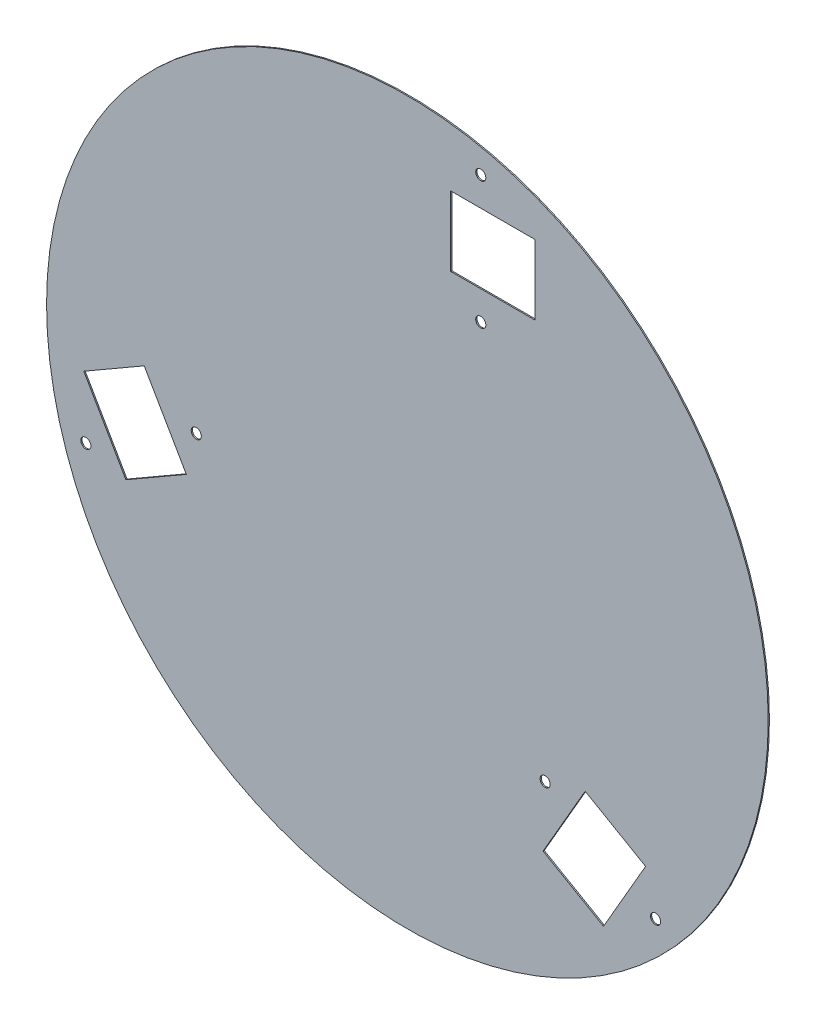
SolidWorks part; units mm, degrees
material "Acier non allié"
ref_plane "Plan de face" through (0, 0, 0) normal (0, 0, 1) x (1, 0, 0)
ref_plane "Plan de dessus" through (0, 0, 0) normal (0, 1, 0) x (1, 0, 0)
ref_plane "Plan de droite" through (0, 0, 0) normal (1, 0, 0) x (0, 0, -1)
sketch "Esquisse8" [suppressed] plane through (0, 0, 0) normal (0, 0, 1) x (1, 0, 0)
  line B0 (-127.0632, 47.6636) -> (-120.3316, 47.6636)
  line B1 (-120.3316, 50.4215) -> (-120.3316, 47.6636)
  line B2 (-127.0632, 50.4215) -> (-120.3316, 50.4215)
  line B3 (-127.0632, 50.4215) -> (-127.0632, 47.6636)
  line B4 (-145.8689, 41.621) -> (-145.8689, 44.3023)
  line B5 (-132.9996, 41.621) -> (-145.8689, 41.621)
  line B6 (-132.9996, 55.9755) -> (-132.9996, 41.621)
  line B7 (-136.1141, 55.9755) -> (-132.9996, 55.9755)
  line B8 (-136.1141, 44.3023) -> (-136.1141, 55.9755)
  line B9 (-145.8689, 44.3023) -> (-136.1141, 44.3023)
  line B10 (-166.6205, 55.9755) -> (-166.6205, 53.1907)
  line B11 (-153.5296, 53.1907) -> (-166.6205, 53.1907)
  line B12 (-153.5296, 55.9755) -> (-153.5296, 53.1907)
  line B13 (-153.5296, 55.9755) -> (-166.6205, 55.9755)
  line B14 (-211.399, 53.1907) -> (-198.3081, 53.1907)
  line B15 (-198.3081, 55.9585) -> (-198.3081, 53.1907)
  line B16 (-211.399, 55.9585) -> (-198.3081, 55.9585)
  line B17 (-211.399, 55.9585) -> (-211.399, 53.1907)
  line B18 (-211.399, 41.621) -> (-198.3081, 41.621)
  line B19 (-198.3081, 44.2943) -> (-198.3081, 41.621)
  line B20 (-207.9561, 44.2943) -> (-198.3081, 44.2943)
  line B21 (-207.9561, 47.6636) -> (-207.9561, 44.2943)
  line B22 (-207.9561, 47.6636) -> (-202.1941, 47.6636)
  line B23 (-202.1941, 50.4215) -> (-202.1941, 47.6636)
  line B24 (-211.399, 50.4215) -> (-202.1941, 50.4215)
  line B25 (-211.399, 50.4215) -> (-211.399, 41.621)
  line B26 (-167.5588, 94.5889) -> (-165.466, 94.5889)
  line B27 (-168.2446, 93.9031) -> (-168.2446, 93.8927)
  line B28 (-168.2446, 93.8927) -> (-164.7802, 93.8927)
  line B29 (-164.7802, 93.9031) -> (-164.7802, 93.8927)
  line B30 (-179.5199, 94.5889) -> (-179.5199, 93.8927)
  line B31 (-176.2471, 93.8927) -> (-179.5199, 93.8927)
  line B32 (-176.2471, 94.5889) -> (-176.2471, 93.8927)
  line B33 (-179.5199, 94.5889) -> (-176.2471, 94.5889)
  line B34 (-187.9744, 91.0002) -> (-184.8699, 91.0002)
  line B35 (-184.8699, 91.6706) -> (-184.8699, 91.0002)
  line B36 (-187.2953, 91.6706) -> (-184.8699, 91.6706)
  line B37 (-187.2953, 94.5889) -> (-187.2953, 91.6706)
  line B38 (-187.9744, 94.5889) -> (-187.2953, 94.5889)
  line B39 (-187.9744, 94.5889) -> (-187.9744, 91.0002)
  line B40 (-182.8118, 91.0002) -> (-182.1258, 91.0002)
  line B41 (-182.1258, 94.5889) -> (-182.1258, 91.0002)
  line B42 (-182.8118, 94.5889) -> (-182.1258, 94.5889)
  line B43 (-182.8118, 94.5889) -> (-182.8118, 91.0002)
  line B44 (-191.2034, 93.2004) -> (-191.2034, 92.5109)
  line B45 (-193.5046, 93.2004) -> (-191.2034, 93.2004)
  line B46 (-193.5046, 93.2004) -> (-193.5046, 91.0002)
  line B47 (-193.5046, 91.0002) -> (-190.2319, 91.0002)
  line B48 (-190.2319, 91.6706) -> (-190.2319, 91.0002)
  line B49 (-192.6439, 91.6706) -> (-190.2319, 91.6706)
  line B50 (-192.6439, 92.5109) -> (-192.6439, 91.6706)
  line B51 (-192.6439, 92.5109) -> (-191.2034, 92.5109)
  line B52 (-193.5046, 93.8927) -> (-190.2319, 93.8927)
  line B53 (-190.2319, 94.5889) -> (-190.2319, 93.8927)
  line B54 (-193.5046, 94.5889) -> (-190.2319, 94.5889)
  line B55 (-193.5046, 94.5889) -> (-193.5046, 93.8927)
  line B56 (-217.8342, 92.5109) -> (-216.3937, 92.5109)
  line B57 (-216.3937, 93.2004) -> (-216.3937, 92.5109)
  line B58 (-218.6949, 93.2004) -> (-216.3937, 93.2004)
  line B59 (-218.6949, 93.2004) -> (-218.6949, 91.0002)
  line B60 (-218.6949, 91.0002) -> (-215.4222, 91.0002)
  line B61 (-215.4222, 91.6686) -> (-215.4222, 91.0002)
  line B62 (-217.8342, 91.6686) -> (-215.4222, 91.6686)
  line B63 (-217.8342, 92.5109) -> (-217.8342, 91.6686)
  line B64 (-218.6949, 93.8927) -> (-215.4222, 93.8927)
  line B65 (-215.4222, 94.5889) -> (-215.4222, 93.8927)
  line B66 (-218.6949, 94.5889) -> (-215.4222, 94.5889)
  line B67 (-218.6949, 94.5889) -> (-218.6949, 93.8927)
  line B68 (-153.6274, 100.4538) -> (-163.9488, 110.7564)
  line B69 (-150.6931, 103.3934) -> (-153.6274, 100.4538)
  line B70 (-158.6273, 111.3265) -> (-150.6931, 103.3934)
  line B71 (-150.6981, 119.2702) -> (-158.6273, 111.3265)
  line B72 (-153.6179, 122.1847) -> (-150.6981, 119.2702)
  line B73 (-163.9498, 111.834) -> (-153.6179, 122.1847)
  line B74 (-212.5077, 91.0002) -> (-210.4149, 91.0002)
  line B75 (-209.7291, 92.5146) -> (-209.7291, 91.686)
  line B76 (-213.1935, 93.2004) -> (-210.4149, 93.2004)
  line B77 (-213.1935, 93.2004) -> (-213.1935, 93.1967)
  line B78 (-212.5077, 92.5109) -> (-210.4149, 92.5109)
  line B79 (-210.4149, 92.5109) -> (-210.4149, 91.6686)
  line B80 (-212.5053, 91.6686) -> (-210.4149, 91.6686)
  line B81 (-212.5053, 92.1003) -> (-212.5053, 91.6686)
  line B82 (-213.1935, 92.1003) -> (-212.5053, 92.1003)
  line B83 (-213.1935, 91.686) -> (-213.1935, 92.1003)
  line B84 (-195.2147, 94.5889) -> (-195.2147, 93.8927)
  line B85 (-199.0185, 94.5889) -> (-195.2147, 94.5889)
  line B86 (-199.0185, 94.5889) -> (-199.0185, 93.8927)
  line B87 (-199.0185, 93.8927) -> (-197.4712, 93.8927)
  line B88 (-197.4712, 93.8927) -> (-197.4712, 91.0002)
  line B89 (-197.4712, 91.0002) -> (-196.7942, 91.0002)
  line B90 (-196.7942, 93.8927) -> (-196.7942, 91.0002)
  line B91 (-196.7942, 93.8927) -> (-195.2147, 93.8927)
  line B92 (-161.3569, 85.3255) -> (-157.5898, 83.0055)
  line B93 (-157.5898, 83.0055) -> (-157.5898, 87.227)
  line B94 (-161.3569, 87.227) -> (-157.5898, 87.227)
  line B95 (-161.3569, 87.227) -> (-161.3569, 85.3255)
  line B96 (-150.3507, 78.4647) -> (-150.3507, 69.7508)
  line B97 (-145.0595, 72.3959) -> (-150.3507, 78.4647)
  line B98 (-139.5033, 78.4647) -> (-145.0595, 72.3959)
  line B99 (-139.5033, 69.7508) -> (-139.5033, 78.4647)
  line B100 (-135.8832, 69.7508) -> (-139.5033, 69.7508)
  line B101 (-135.8832, 87.6265) -> (-135.8832, 69.7508)
  line B102 (-145.0509, 77.9984) -> (-135.8832, 87.6265)
  line B103 (-154.0819, 87.8508) -> (-145.0509, 77.9984)
  line B104 (-154.0819, 69.7508) -> (-154.0819, 87.8508)
  line B105 (-154.0819, 69.7508) -> (-150.3507, 69.7508)
  line B106 (-121.0636, 82.5326) -> (-116.4642, 82.5326)
  line B107 (-132.5484, 82.5326) -> (-127.949, 82.5326)
  line B108 (-238.7768, 62.4441) -> (-69.387, 62.4441)
  line B109 (-69.387, 63.243) -> (-69.387, 62.4441)
  line B110 (-238.7768, 63.243) -> (-69.387, 63.243)
  line B111 (-238.7768, 63.243) -> (-238.7768, 62.4441)
  line B112 (-91.2664, 69.7508) -> (-87.3469, 69.7508)
  line B113 (-87.3469, 82.5326) -> (-87.3469, 69.7508)
  line B114 (-91.2664, 82.5326) -> (-87.3469, 82.5326)
  line B115 (-91.2664, 69.7508) -> (-91.2664, 82.5326)
  line B116 (-96.0285, 83.7433) -> (-82.8413, 83.7433)
  line B117 (-82.8413, 83.7433) -> (-82.8413, 87.227)
  line B118 (-96.0285, 87.227) -> (-82.8413, 87.227)
  line B119 (-96.0285, 87.227) -> (-96.0285, 83.7433)
  line B120 (-204.5437, 87.227) -> (-199.3625, 77.1943)
  line B121 (-209.7167, 77.1943) -> (-204.5437, 87.227)
  line B122 (-209.7167, 77.1943) -> (-205.6679, 77.1943)
  line B123 (-204.5437, 79.3746) -> (-205.6679, 77.1943)
  line B124 (-203.4177, 77.1943) -> (-204.5437, 79.3746)
  line B125 (-203.4177, 77.1943) -> (-199.3625, 77.1943)
  line B126 (-213.7549, 76.677) -> (-219.9317, 76.677)
  line B127 (-213.7549, 80.1113) -> (-213.7549, 76.677)
  line B128 (-219.9317, 80.1113) -> (-213.7549, 80.1113)
  line B129 (-219.9317, 82.5326) -> (-219.9317, 80.1113)
  line B130 (-223.6873, 82.5326) -> (-219.9317, 82.5326)
  line B131 (-223.6873, 69.8839) -> (-223.6873, 82.5326)
  line B132 (-219.9317, 69.8839) -> (-223.6873, 69.8839)
  line B133 (-219.9317, 76.677) -> (-219.9317, 69.8839)
  line B134 (-168.2446, 93.2004) -> (-165.466, 93.2004)
  line B135 (-168.2446, 93.2004) -> (-168.2446, 93.1967)
  line B136 (-167.5588, 92.5109) -> (-165.466, 92.5109)
  line B137 (-165.466, 92.5109) -> (-165.466, 91.6686)
  line B138 (-167.5564, 91.6686) -> (-165.466, 91.6686)
  line B139 (-167.5564, 92.1003) -> (-167.5564, 91.6686)
  line B140 (-168.2446, 92.1003) -> (-167.5564, 92.1003)
  line B141 (-168.2446, 91.686) -> (-168.2446, 92.1003)
  line B142 (-167.5588, 91.0002) -> (-165.466, 91.0002)
  line B143 (-164.7802, 92.5146) -> (-164.7802, 91.686)
  line B144 (-213.486, 69.8839) -> (-209.4372, 69.8839)
  line B145 (-208.071, 72.5336) -> (-209.4372, 69.8839)
  line B146 (-208.071, 72.5336) -> (-201.0108, 72.5336)
  line B147 (-199.5737, 69.7508) -> (-201.0108, 72.5336)
  line B148 (-195.5185, 69.7508) -> (-199.5737, 69.7508)
  line B149 (-198.728, 75.9657) -> (-195.5185, 69.7508)
  line B150 (-210.3501, 75.9657) -> (-198.728, 75.9657)
  line B151 (-213.486, 69.8839) -> (-210.3501, 75.9657)
  line B152 (-189.8395, 83.7433) -> (-182.0909, 83.7433)
  line B153 (-184.9396, 86.7348) -> (-186.4712, 87.2271)
  line B154 (-193.6657, 87.2271) -> (-186.4712, 87.2271)
  line B155 (-193.6657, 87.2271) -> (-193.6657, 77.1944)
  line B156 (-193.6657, 77.1944) -> (-186.2925, 77.1944)
  line B157 (-189.8668, 73.1972) -> (-186.3883, 73.1972)
  line B158 (-189.8668, 75.9658) -> (-189.8668, 73.1972)
  line B159 (-193.6657, 75.9658) -> (-189.8668, 75.9658)
  line B160 (-193.6657, 75.9658) -> (-193.6657, 69.7508)
  line B161 (-193.6657, 69.7508) -> (-185.6203, 69.7508)
  line B162 (-185.7395, 82.5327) -> (-181.9445, 82.5327)
  line B163 (-189.8395, 80.2675) -> (-187.1218, 80.2675)
  line B164 (-189.8395, 83.7433) -> (-189.8395, 80.2675)
  line B165 (-174.0652, 83.7433) -> (-165.2782, 83.7433)
  line B166 (-168.6352, 86.6749) -> (-170.5726, 87.227)
  line B167 (-177.791, 87.227) -> (-170.5726, 87.227)
  line B168 (-177.791, 87.227) -> (-177.791, 69.7508)
  line B169 (-177.791, 69.7508) -> (-174.0652, 69.7508)
  line B170 (-174.0652, 69.7508) -> (-174.0652, 75.9657)
  line B171 (-174.0652, 75.9657) -> (-171.5983, 75.9657)
  line B172 (-171.5983, 75.9657) -> (-167.9913, 69.7508)
  line B173 (-167.9913, 69.7508) -> (-163.5264, 69.7508)
  line B174 (-163.5264, 69.7508) -> (-167.7035, 76.7107)
  line B175 (-168.6352, 82.5327) -> (-164.8908, 82.5327)
  line B176 (-174.0652, 79.6101) -> (-170.7412, 79.6101)
  line B177 (-174.0652, 83.7433) -> (-174.0652, 79.6101)
  line B178 (-288.9204, 52.2277) -> (-271.4204, 21.9168)
  line B179 (-271.4204, 21.9168) -> (-246.3057, 36.4168)
  line B180 (-246.3057, 36.4168) -> (-263.8057, 66.7277)
  line B181 (-263.8057, 66.7277) -> (-288.9204, 52.2277)
  line B182 (-80.4996, 5.2399) -> (-97.9996, -25.071)
  line B183 (-97.9996, -25.071) -> (-72.8848, -39.571)
  line B184 (-72.8848, -39.571) -> (-55.3848, -9.2601)
  line B185 (-55.3848, -9.2601) -> (-80.4996, 5.2399)
  line B186 (-136.4026, 164.4207) -> (-101.4026, 164.4207)
  line B187 (-101.4026, 164.4207) -> (-101.4026, 193.4207)
  line B188 (-101.4026, 193.4207) -> (-136.4026, 193.4207)
  line B189 (-136.4026, 193.4207) -> (-136.4026, 164.4207)
  line B190 (-154.5679, 130.5213) -> (-174.01, 111.0768)
  line B191 (-154.4915, 91.5608) -> (-174.01, 111.0768)
  line B192 (-153.4138, 91.5609) -> (-129.6531, 115.3246)
  line B193 (-129.6532, 116.4022) -> (-153.5146, 140.2606)
  line B194 (-178.3529, 116.4968) -> (-154.5922, 140.2605)
  line B195 (-175.9678, 113.0343) -> (-178.3528, 115.4191)
  line B196 (-175.9678, 113.0343) -> (-153.9526, 135.0523)
  line B197 (-153.9526, 135.0523) -> (-134.8557, 115.9579)
  line B198 (-134.8557, 115.9579) -> (-153.9526, 96.8586)
  line B199 (-153.9526, 96.8586) -> (-168.2078, 111.112)
  line B200 (-168.2078, 111.112) -> (-151.1453, 128.1767)
  line B201 (-151.1453, 128.1767) -> (-153.4903, 130.5214)
  line B202 (-161.3569, 69.7508) -> (-157.5898, 69.7508)
  line B203 (-157.5898, 80.7086) -> (-157.5898, 69.7508)
  line B204 (-161.3569, 83.0055) -> (-157.5898, 80.7086)
  line B205 (-161.3569, 83.0055) -> (-161.3569, 69.7508)
  line B206 (-212.2972, 87.227) -> (-223.6873, 87.227)
  line B207 (-223.6873, 87.227) -> (-223.6873, 83.7433)
  line B208 (-223.6873, 83.7433) -> (-212.2972, 83.7433)
  line B209 (-212.2972, 83.7433) -> (-212.2972, 87.227)
  line B210 (-113.2245, 69.7508) -> (-109.375, 69.7508)
  line B211 (-109.375, 79.5134) -> (-109.375, 69.7508)
  line B212 (-97.8943, 69.04) -> (-109.375, 79.5134)
  line B213 (-97.8943, 87.227) -> (-97.8943, 69.04)
  line B214 (-101.6626, 87.227) -> (-97.8943, 87.227)
  line B215 (-101.6626, 87.227) -> (-101.6626, 77.3224)
  line B216 (-101.6626, 77.3224) -> (-113.2245, 87.8508)
  line B217 (-113.2245, 87.8508) -> (-113.2245, 69.7508)
  line B218 (-131.8111, 83.7433) -> (-117.2015, 83.7433)
  line B219 (-201.2358, 91.8292) -> (-200.8109, 91.0002)
  line B220 (-200.8109, 91.0002) -> (-200.0223, 91.0002)
  line B221 (-201.9653, 94.5889) -> (-200.0223, 91.0002)
  line B222 (-202.6502, 94.5889) -> (-201.9653, 94.5889)
  line B223 (-202.6502, 94.5889) -> (-201.5852, 92.5109)
  line B224 (-203.4892, 92.5109) -> (-201.5852, 92.5109)
  line B225 (-204.4284, 91.0002) -> (-203.4892, 92.5109)
  line B226 (-204.4284, 91.0002) -> (-203.6929, 91.0002)
  line B227 (-203.6929, 91.0002) -> (-203.2078, 91.8292)
  line B228 (-203.2078, 91.8292) -> (-201.2358, 91.8292)
  line B229 (-212.5077, 94.5889) -> (-210.4149, 94.5889)
  line B230 (-213.1935, 93.9031) -> (-213.1935, 93.8927)
  line B231 (-213.1935, 93.8927) -> (-209.7291, 93.8927)
  line B232 (-223.0488, 94.5889) -> (-223.8274, 94.5889)
  line B233 (-223.8274, 94.5889) -> (-223.8274, 91.0002)
  line B234 (-223.8274, 91.0002) -> (-220.6101, 91.0002)
  line B235 (-220.6101, 91.0002) -> (-220.6101, 91.6706)
  line B236 (-220.6101, 91.6706) -> (-223.0488, 91.6706)
  line B237 (-223.0488, 91.6706) -> (-223.0488, 94.5889)
  line B238 (-179.5199, 91.0002) -> (-176.2471, 91.0002)
  line B239 (-176.2471, 91.6706) -> (-176.2471, 91.0002)
  line B240 (-178.6591, 91.6706) -> (-176.2471, 91.6706)
  line B241 (-178.6591, 92.5109) -> (-178.6591, 91.6706)
  line B242 (-178.6591, 92.5109) -> (-177.2186, 92.5109)
  line B243 (-177.2186, 93.2004) -> (-177.2186, 92.5109)
  line B244 (-179.5199, 93.2004) -> (-177.2186, 93.2004)
  line B245 (-179.5199, 93.2004) -> (-179.5199, 91.0002)
  line B246 (-170.5964, 93.9031) -> (-170.5964, 93.034)
  line B247 (-174.0031, 94.5889) -> (-171.2822, 94.5889)
  line B248 (-174.0031, 94.5889) -> (-174.0031, 93.8927)
  line B249 (-174.0031, 93.8927) -> (-171.2606, 93.8927)
  line B250 (-171.2606, 93.8927) -> (-171.2606, 92.8686)
  line B251 (-174.0031, 92.8686) -> (-171.2606, 92.8686)
  line B252 (-174.0031, 92.8686) -> (-174.0031, 91.0002)
  line B253 (-174.0031, 91.0002) -> (-173.2075, 91.0002)
  line B254 (-173.2075, 91.0002) -> (-173.2075, 92.3386)
  line B255 (-173.2075, 92.3386) -> (-172.4075, 92.3386)
  line B256 (-172.4075, 92.3386) -> (-171.1064, 91.0002)
  line B257 (-171.1064, 91.0002) -> (-170.1619, 91.0002)
  line B258 (-171.5695, 92.3482) -> (-170.1619, 91.0002)
  line B259 (-171.5695, 92.3482) -> (-171.2822, 92.3482)
  line B260 (-184.4889, 41.6039) -> (-180.44, 41.6039)
  line B261 (-175.5356, 55.9585) -> (-180.44, 41.6039)
  line B262 (-175.5356, 55.9585) -> (-178.8962, 55.9585)
  line B263 (-178.8962, 55.9585) -> (-182.4645, 46.0889)
  line B264 (-186.0328, 55.9585) -> (-182.4645, 46.0889)
  line B265 (-189.3933, 55.9585) -> (-186.0328, 55.9585)
  line B266 (-189.3933, 55.9585) -> (-184.4889, 41.6039)
  line B267 (-219.0597, 44.3023) -> (-228.8145, 44.3023)
  line B268 (-228.8145, 44.3023) -> (-228.8145, 55.9755)
  line B269 (-228.8145, 55.9755) -> (-231.9291, 55.9755)
  line B270 (-231.9291, 55.9755) -> (-231.9291, 41.621)
  line B271 (-231.9291, 41.621) -> (-219.0597, 41.621)
  line B272 (-219.0597, 41.621) -> (-219.0597, 44.3023)
  line B273 (-166.6205, 44.2943) -> (-166.6205, 41.621)
  line B274 (-153.5296, 41.621) -> (-166.6205, 41.621)
  line B275 (-153.5296, 50.4215) -> (-153.5296, 41.621)
  line B276 (-153.5296, 50.4215) -> (-162.7345, 50.4215)
  line B277 (-162.7345, 50.4215) -> (-162.7345, 47.6636)
  line B278 (-156.9725, 47.6636) -> (-162.7345, 47.6636)
  line B279 (-156.9725, 47.6636) -> (-156.9725, 44.2943)
  line B280 (-156.9725, 44.2943) -> (-166.6205, 44.2943)
  line B281 (-100.191, 45.2326) -> (-100.191, 55.9755)
  line B282 (-100.191, 55.9755) -> (-103.5515, 55.9755)
  line B283 (-103.5515, 55.9755) -> (-103.5515, 46.3026)
  line B284 (-104.5675, 45.2866) -> (-109.6721, 45.2866)
  line B285 (-110.6881, 55.9755) -> (-110.6881, 46.3026)
  line B286 (-114.0487, 55.9755) -> (-110.6881, 55.9755)
  line B287 (-114.0487, 55.9755) -> (-114.0487, 45.2326)
  line B288 (-110.4927, 41.6766) -> (-103.747, 41.6766)
  line B289 (-94.6217, 39.3739) -> (-94.6509, 42.6897)
  line B290 (-93.0123, 39.3739) -> (-94.6217, 39.3739)
  line B291 (-93.0123, 40.2363) -> (-93.0123, 39.3739)
  line B292 (-86.3102, 40.2363) -> (-86.3102, 39.3739)
  line B293 (-79.4589, 39.3739) -> (-86.3102, 39.3739)
  line B294 (-85.2131, 50.2165) -> (-79.6533, 49.7729)
  line B295 (-84.6443, 58.1294) -> (-84.6541, 56.0136)
  line B296 (-74.6215, 59.3901) -> (-74.6712, 56.0136)
  line B297 (-74.6215, 59.3901) -> (-76.3113, 59.3901)
  line B298 (-76.3113, 58.5492) -> (-76.3113, 59.3901)
  line B299 (-82.9953, 58.5492) -> (-82.9953, 59.3901)
  line B300 (-82.9953, 59.3901) -> (-90.0707, 59.3901)
  line B301 (-90.0707, 49.0324) -> (-84.0158, 48.4974)
  line B302 (-84.6443, 40.6403) -> (-84.6211, 42.6897)
  circle B303 centre (-154.4026, 68.6925) radius 150
  arc B304 (-240.0634, 53.2421) -> (-244.2634, 53.2421) centre (-242.1634, 53.2421) ccw
  arc B305 (-244.2634, 53.2421) -> (-240.0634, 53.2421) centre (-242.1634, 53.2421) ccw
  arc B306 (-285.9627, 26.7421) -> (-290.1627, 26.7421) centre (-288.0627, 26.7421) ccw
  arc B307 (-290.1627, 26.7421) -> (-285.9627, 26.7421) centre (-288.0627, 26.7421) ccw
  arc B308 (-95.0419, 0.4146) -> (-99.2419, 0.4146) centre (-97.1419, 0.4146) ccw
  arc B309 (-99.2419, 0.4146) -> (-95.0419, 0.4146) centre (-97.1419, 0.4146) ccw
  arc B310 (-49.1425, -26.0854) -> (-53.3425, -26.0854) centre (-51.2425, -26.0854) ccw
  arc B311 (-53.3425, -26.0854) -> (-49.1425, -26.0854) centre (-51.2425, -26.0854) ccw
  arc B312 (-126.0026, 152.4207) -> (-121.8026, 152.4207) centre (-123.9026, 152.4207) ccw
  arc B313 (-121.8026, 152.4207) -> (-126.0026, 152.4207) centre (-123.9026, 152.4207) ccw
  arc B314 (-121.8026, 205.4207) -> (-126.0026, 205.4207) centre (-123.9026, 205.4207) ccw
  arc B315 (-126.0026, 205.4207) -> (-121.8026, 205.4207) centre (-123.9026, 205.4207) ccw
  arc B316 (-167.5588, 94.5889) -> (-168.2446, 93.9031) centre (-167.5588, 93.9031) ccw
  arc B317 (-164.7802, 93.9031) -> (-165.466, 94.5889) centre (-165.466, 93.9031) ccw
  arc B318 (-163.9498, 111.834) -> (-163.9488, 110.7564) centre (-163.4105, 111.2957) ccw
  arc B319 (-210.4149, 91.0002) -> (-209.7291, 91.686) centre (-210.4149, 91.686) ccw
  arc B320 (-209.7291, 92.5146) -> (-210.4149, 93.2004) centre (-210.4149, 92.5146) ccw
  arc B321 (-213.1935, 93.1967) -> (-212.5077, 92.5109) centre (-212.5077, 93.1967) ccw
  arc B322 (-213.1935, 91.686) -> (-212.5077, 91.0002) centre (-212.5077, 91.686) ccw
  arc B323 (-127.949, 82.5326) -> (-121.0636, 82.5326) centre (-124.5063, 78.4647) ccw
  arc B324 (-132.5484, 82.5326) -> (-116.4642, 82.5326) centre (-124.5063, 78.4647) ccw
  arc B325 (-168.2446, 93.1967) -> (-167.5588, 92.5109) centre (-167.5588, 93.1967) ccw
  arc B326 (-168.2446, 91.686) -> (-167.5588, 91.0002) centre (-167.5588, 91.686) ccw
  arc B327 (-165.466, 91.0002) -> (-164.7802, 91.686) centre (-165.466, 91.686) ccw
  arc B328 (-164.7802, 92.5146) -> (-165.466, 93.2004) centre (-165.466, 92.5146) ccw
  arc B329 (-182.0909, 83.7433) -> (-184.9396, 86.7348) centre (-186.2605, 82.6249) ccw
  arc B330 (-186.3883, 73.1972) -> (-186.2925, 77.1944) centre (-186.3883, 75.197) ccw
  arc B331 (-185.6203, 69.7508) -> (-183.6465, 79.1893) centre (-185.554, 74.6626) ccw
  arc B332 (-183.6465, 79.1893) -> (-181.9445, 82.5327) centre (-186.2605, 82.6249) ccw
  arc B333 (-187.1218, 80.2675) -> (-185.7395, 82.5327) centre (-187.3882, 81.9844) ccw
  arc B334 (-165.2782, 83.7433) -> (-168.6352, 86.6749) centre (-170.1926, 81.5036) ccw
  arc B335 (-167.7035, 76.7107) -> (-164.8908, 82.5327) centre (-170.1926, 81.5036) ccw
  arc B336 (-170.7412, 79.6101) -> (-168.6352, 82.5327) centre (-170.7412, 81.8302) ccw
  arc B337 (-53.3425, -26.0854) -> (-49.1425, -26.0854) centre (-51.2425, -26.0854) ccw
  arc B338 (-126.0026, 152.4207) -> (-121.8026, 152.4207) centre (-123.9026, 152.4207) ccw
  arc B339 (-126.0026, 205.4207) -> (-121.8026, 205.4207) centre (-123.9026, 205.4207) ccw
  arc B340 (-244.2634, 53.2421) -> (-240.0634, 53.2421) centre (-242.1634, 53.2421) ccw
  arc B341 (-99.2419, 0.4146) -> (-95.0419, 0.4146) centre (-97.1419, 0.4146) ccw
  arc B342 (-290.1627, 26.7421) -> (-285.9627, 26.7421) centre (-288.0627, 26.7421) ccw
  arc B343 (-4.4026, 68.6925) -> (-304.4026, 68.6925) centre (-154.4026, 68.6925) ccw
  arc B344 (-153.4903, 130.5214) -> (-154.5679, 130.5213) centre (-154.0291, 129.9826) ccw
  arc B345 (-154.4915, 91.5608) -> (-153.4138, 91.5609) centre (-153.9527, 92.0996) ccw
  arc B346 (-129.6531, 115.3246) -> (-129.6532, 116.4022) centre (-130.192, 115.8634) ccw
  arc B347 (-153.5146, 140.2606) -> (-154.5922, 140.2605) centre (-154.0534, 139.7217) ccw
  arc B348 (-178.3529, 116.4968) -> (-178.3528, 115.4191) centre (-177.8141, 115.958) ccw
  arc B349 (-117.2015, 83.7433) -> (-131.8111, 83.7433) centre (-124.5063, 78.4647) ccw
  arc B350 (-209.7291, 93.8927) -> (-210.4149, 94.5889) centre (-210.4148, 93.9031) ccw
  arc B351 (-212.5077, 94.5889) -> (-213.1935, 93.9031) centre (-212.5077, 93.9031) ccw
  arc B352 (-171.2822, 92.3482) -> (-170.5964, 93.034) centre (-171.2822, 93.034) ccw
  arc B353 (-170.5964, 93.9031) -> (-171.2822, 94.5889) centre (-171.2822, 93.9031) ccw
  arc B354 (-103.747, 41.6766) -> (-100.191, 45.2326) centre (-103.747, 45.2326) ccw
  arc B355 (-104.5675, 45.2866) -> (-103.5515, 46.3026) centre (-104.5675, 46.3026) ccw
  arc B356 (-110.6881, 46.3026) -> (-109.6721, 45.2866) centre (-109.6721, 46.3026) ccw
  arc B357 (-114.0487, 45.2326) -> (-110.4927, 41.6766) centre (-110.4927, 45.2326) ccw
  arc B358 (-84.6211, 42.6897) -> (-94.6509, 42.6897) centre (-89.636, 42.6897) ccw
  arc B359 (-86.3102, 40.2363) -> (-93.0123, 40.2363) centre (-89.6613, 40.2363) ccw
  arc B360 (-79.4589, 39.3739) -> (-79.6533, 49.7729) centre (-79.8673, 44.5676) ccw
  arc B361 (-84.6443, 58.1294) -> (-85.2131, 50.2165) centre (-84.5768, 54.1477) ccw
  arc B362 (-84.6541, 56.0136) -> (-74.6712, 56.0136) centre (-79.6627, 56.0136) ccw
  arc B363 (-82.9953, 58.5492) -> (-76.3113, 58.5492) centre (-79.6533, 58.5492) ccw
  arc B364 (-90.0707, 59.3901) -> (-90.0707, 49.0324) centre (-89.4645, 54.2112) ccw
  arc B365 (-84.6443, 40.6403) -> (-84.0158, 48.4974) centre (-84.5936, 44.5899) ccw
sketch_block_instance "Base_ (1)-1"
sketch_block "Base_ (1)"
other "Objet de détail2"
extrude "Boss.-Extru.2" [suppressed] add sketch "Esquisse8" along normal blind 3.175 contours B303 B357 B287 B286 B285 B356 B284 B355 B283 B282 B281 B354 B288 B353 B246 B352 B259 B258 B257 B256 B255 B254 B253 B252 B251 B250 B249 B248 B247 B351 B229 B350 B231 B230 B349 B218 B348 B194 B347 B193 B346 B192 B345 B191 B190
sketch "Esquisse1" plane through (0, 0, 0) normal (0, 0, 1) x (1, 0, 0)
  circle A0 centre (0, 0) radius 150
  dimension "D1" = 300
extrude "Boss.-Extru.1" add sketch "Esquisse1" along normal blind 0.5
sketch "Esquisse2" plane through (0, 0, 0.5) normal (0, 0, 1) x (1, 0, 0)
  line L1 (-37.5, -52.75) -> (37.5, -52.75)
  line L2 (-37.5, -52.75) -> (-37.5, 52.75)
  line L3 (-37.5, 52.75) -> (37.5, 52.75)
  line L4 (37.5, -52.75) -> (37.5, 52.75)
  line L5 (-37.5, -52.75) -> (37.5, 52.75) construction
  line L6 (-37.5, 52.75) -> (37.5, -52.75) construction
  circle A0 centre (-33, 48.25) radius 2
  circle A1 centre (33, 48.25) radius 2
  circle A2 centre (-33, -48.25) radius 2
  circle A3 centre (33, -48.25) radius 2
  point P0 (0, 0)
  dimension "D3" = 4
  dimension "D5" = 4.5
  dimension "D6" = 4.5
  dimension "D7" = 4.5
  dimension "D8" = 4.5
  dimension "D9" = 4.5
  dimension "D10" = 4.5
  dimension "D11" = 4.5
  dimension "D1" = 105.5
  dimension "D2" = 75
  dimension "D4" = 4.5
sketch "Esquisse5" plane through (0, 0, 0.5) normal (0, 0, 1) x (1, 0, 0)
  line L0 (0, 133.3333) -> (-115.4701, -66.6667)
  line L1 (-115.4701, -66.6667) -> (115.4701, -66.6667)
  line L2 (115.4701, -66.6667) -> (0, 133.3333)
  line L3 (0, 133.3333) -> (-22, 95.2282)
  line L4 (-22, 95.2282) -> (22, 95.2282)
  line L5 (22, 95.2282) -> (0, 133.3333)
  line L6 (-115.4701, -66.6667) -> (-93.4701, -28.5615)
  line L7 (-93.4701, -28.5615) -> (-71.4701, -66.6667)
  line L8 (-71.4701, -66.6667) -> (-115.4701, -66.6667)
  line L9 (115.4701, -66.6667) -> (71.4701, -66.6667)
  line L10 (71.4701, -66.6667) -> (93.4701, -28.5615)
  line L11 (93.4701, -28.5615) -> (115.4701, -66.6667)
  line L12 (0, 0) -> (0, 133.3333) construction
  line L13 (-115.4701, -66.6667) -> (0, 0) construction
  line L14 (0, 0) -> (115.4701, -66.6667) construction
  dimension "D1" = 200
  dimension "D2" = 133.3333
  dimension "D3" = 44
sketch "Esquisse6" plane through (0, 0, 0.5) normal (0, 0, 1) x (1, 0, 0)
  line L0 (-22, 95.2282) -> (22, 95.2282) construction
  line L1 (18, 124.7282) -> (53, 124.7282)
  line L2 (18, 124.7282) -> (18, 95.7282)
  line L3 (18, 95.7282) -> (53, 95.7282)
  line L4 (53, 124.7282) -> (53, 95.7282)
  line L5 (73.9031, -63.4526) -> (56.4031, -93.7635)
  line L6 (56.4031, -93.7635) -> (81.5178, -108.2635)
  line L7 (81.5178, -108.2635) -> (99.0178, -77.9526)
  line L8 (99.0178, -77.9526) -> (73.9031, -63.4526)
  line L9 (71.4701, -66.6667) -> (93.4701, -28.5615) construction
  line L10 (-109.4031, -1.9648) -> (-91.9031, -32.2757)
  line L11 (-91.9031, -32.2757) -> (-117.0178, -46.7757)
  line L12 (-117.0178, -46.7757) -> (-134.5178, -16.4648)
  line L13 (-134.5178, -16.4648) -> (-109.4031, -1.9648)
  line L14 (-93.4701, -28.5615) -> (-71.4701, -66.6667) construction
  point P6 (0, 95.2282)
  point P7 (18, 110.2282)
  point P14 (82.4701, -47.6141)
  point P15 (86.4604, -70.7026)
  point P22 (-104.4604, -39.5257)
  point P23 (-82.4701, -47.6141)
  dimension "D1" = 29
  dimension "D2" = 35
  dimension "D3" = 18
  dimension "D4" = 15
  dimension "D5" = 29
  dimension "D6" = 35
  dimension "D7" = 18
  dimension "D8" = 15
  dimension "D9" = 35
  dimension "D10" = 29
  dimension "D11" = 15
  dimension "D12" = 18
extrude "Enlèv. mat.-Extru.2" cut sketch "Esquisse6" against normal blind 3.175
sketch "Esquisse7" plane through (0, 0, 0.5) normal (0, 0, 1) x (1, 0, 0)
  line L1 (-91.9031, -32.2757) -> (-109.4031, -1.9648) construction
  line L2 (-117.0178, -46.7757) -> (-91.9031, -32.2757) construction
  line L4 (73.9031, -63.4526) -> (56.4031, -93.7635) construction
  line L5 (99.0178, -77.9526) -> (73.9031, -63.4526) construction
  line L6 (81.5178, -108.2635) -> (99.0178, -77.9526) construction
  line L8 (53, 124.7282) -> (18, 124.7282) construction
  line L9 (18, 124.7282) -> (18, 95.7282) construction
  line L11 (-134.5178, -16.4648) -> (-117.0178, -46.7757) construction
  line L12 (18, 95.7282) -> (53, 95.7282) construction
  circle A0 centre (-133.6601, -41.9503) radius 2.1
  circle A1 centre (-87.7608, -15.4503) radius 2.1
  circle A2 centre (30.5, 136.7282) radius 2.1
  circle A3 centre (30.5, 83.7282) radius 2.1
  circle A5 centre (103.1601, -94.7779) radius 2.1
  circle A6 centre (57.2608, -68.2779) radius 2.1
  dimension "D1" = 4.2
  dimension "D3" = 12
  dimension "D5" = 12.5
  dimension "D6" = 12
  dimension "D8" = 12
  dimension "D9" = 12.5
  dimension "D10" = 12
  dimension "D12" = 12.5
  dimension "D2" = 12
  dimension "D4" = 12.5
  dimension "D7" = 12.5
  dimension "D11" = 12.5
  dimension "D13" = 12
extrude "Enlèv. mat.-Extru.3" cut sketch "Esquisse7" against normal through all
